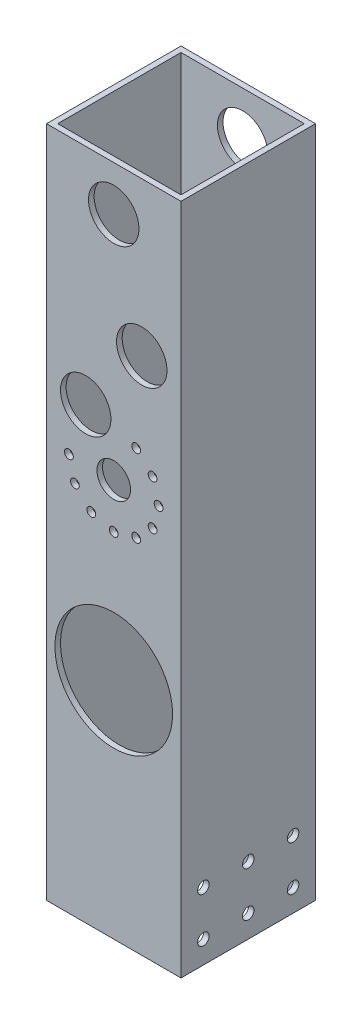
SolidWorks part; units mm, degrees
ref_plane "Front Plane" through (0, 0, 0) normal (0, 0, 1) x (1, 0, 0)
ref_plane "Top Plane" through (0, 0, 0) normal (0, 1, 0) x (1, 0, 0)
ref_plane "Right Plane" through (0, 0, 0) normal (1, 0, 0) x (0, 0, -1)
sketch "Sketch1" plane through (0, 0, 0) normal (0, 1, 0) x (1, 0, 0)
  line L0 (-34.925, -34.925) -> (-34.925, 34.925)
  line L1 (-38.1, -38.1) -> (38.1, -38.1)
  line L2 (-38.1, -38.1) -> (-38.1, 38.1)
  line L3 (-38.1, 38.1) -> (38.1, 38.1)
  line L4 (38.1, -38.1) -> (38.1, 38.1)
  line L5 (-38.1, -38.1) -> (38.1, 38.1) construction
  line L6 (-38.1, 38.1) -> (38.1, -38.1) construction
  line L7 (-34.925, 34.925) -> (34.925, 34.925)
  line L8 (34.925, -34.925) -> (34.925, 34.925)
  line L9 (-34.925, -34.925) -> (34.925, -34.925)
  point P0 (0, 0)
  dimension "D1" = 76.2
  dimension "D2" = 76.2
  dimension "D3" = 3.175
extrude "Boss-Extrude1" add sketch "Sketch1" along normal blind 381
sketch "Sketch2" plane through (0, 0, -38.1) normal (0, 0, -1) x (-1, 0, 0)
  line L0 (-38.1, 381) -> (38.1, 381) construction
  line L1 (-38.1, 381) -> (-38.1, 0) construction
  circle A0 centre (0, 355.6) radius 14.2875
  circle A1 centre (0, 127) radius 9.525
  circle A2 centre (0, 127) radius 25.4 construction
  circle A3 centre (0, 152.4) radius 2.4892
  circle A4 centre (12.7, 148.997) radius 2.4892
  circle A5 centre (21.997, 139.7) radius 2.4892
  circle A6 centre (25.4, 127) radius 2.4892
  circle A7 centre (21.997, 114.3) radius 2.4892
  circle A8 centre (12.7, 105.003) radius 2.4892
  circle A9 centre (0, 101.6) radius 2.4892
  circle A10 centre (-12.7, 105.003) radius 2.4892
  circle A11 centre (-21.997, 114.3) radius 2.4892
  circle A12 centre (-25.4, 127) radius 2.4892
  circle A13 centre (-21.997, 139.7) radius 2.4892
  circle A14 centre (-12.7, 148.997) radius 2.4892
  point P34 (0, 127)
  dimension "D1" = 28.575
  dimension "D4" = 19.05
  dimension "D5" = 50.8
  dimension "D6" = 4.9784
  dimension "D2" = 25.4
  dimension "D3" = 228.6
  dimension "D8" = 12.7
  dimension "D9" = 3.403
  dimension "D10" = 38.1
  dimension "D7" = 12
extrude "Cut-Extrude1" cut sketch "Sketch2" against normal blind 304.8
sketch "Sketch3" plane through (0, 0, 38.1) normal (0, 0, 1) x (1, 0, 0)
  circle A0 centre (0, 127) radius 33.3375
  dimension "D1" = 66.675
extrude "Cut-Extrude2" cut sketch "Sketch3" against normal blind 47.625
sketch "Sketch5" plane through (0, 0, -38.1) normal (0, 0, -1) x (-1, 0, 0)
  line L0 (-38.1, 381) -> (-38.1, 0) construction
  circle A0 centre (-15.875, 294.0377) radius 14.2875
  circle A1 centre (15.875, 254.2844) radius 14.2875
  circle A2 centre (0, 225.244) radius 9.525
  circle A3 centre (0, 355.6) radius 14.2875 construction
  dimension "D4" = 19.05
  dimension "D1" = 63.5762
  dimension "D2" = 50.8762
  dimension "D3" = 33.0962
  dimension "D5" = 22.225
  dimension "D6" = 53.975
  dimension "D7" = 38.1
extrude "Cut-Extrude3" cut sketch "Sketch5" against normal blind 83.185
sketch "Sketch6" plane through (0, 0, -38.1) normal (0, 0, -1) x (-1, 0, 0)
  circle A0 centre (0, 225.244) radius 33.3375
  dimension "D1" = 66.675
extrude "Cut-Extrude4" cut sketch "Sketch6" against normal blind 47.625
sketch "Sketch7" plane through (0, 0, 38.1) normal (0, 0, 1) x (1, 0, 0)
  circle A0 centre (0, 225.244) radius 25.4 construction
  circle A1 centre (0, 199.844) radius 2.4892
  circle A2 centre (-12.7, 203.247) radius 2.4892
  circle A3 centre (-21.997, 212.544) radius 2.4892
  circle A4 centre (-25.4, 225.244) radius 2.4892
  circle A5 centre (-21.997, 237.944) radius 2.4892 [skipped]
  circle A6 centre (-12.7, 247.2411) radius 2.4892 [skipped]
  circle A7 centre (0, 250.644) radius 2.4892 [skipped]
  circle A8 centre (12.7, 247.2411) radius 2.4892
  circle A9 centre (21.997, 237.944) radius 2.4892
  circle A10 centre (25.4, 225.244) radius 2.4892
  circle A11 centre (21.997, 212.544) radius 2.4892
  circle A12 centre (12.7, 203.247) radius 2.4892
  point P30 (0, 225.244)
  dimension "D1" = 50.8
  dimension "D2" = 4.9784
  dimension "D3" = 12
extrude "Cut-Extrude5" cut sketch "Sketch7" against normal blind 47.625
sketch "Sketch10" plane through (-38.1, 0, 0) normal (-1, 0, 0) x (0, 0, 1)
  line L0 (-38.1, 93.6625) -> (38.1, 93.6625) construction
  line L1 (-38.1, 381) -> (-38.1, 0) construction
  line L2 (38.1, 381) -> (38.1, 0) construction
  line L3 (-38.1, 0) -> (38.1, 0) construction
  line L4 (0, 93.6625) -> (0, 0) construction
  line L5 (-38.1, 50.8) -> (38.1, 50.8) construction
  circle A0 centre (-25.4, 12.7) radius 3.2639
  circle A1 centre (0, 12.7) radius 3.2639
  circle A2 centre (25.4, 12.7) radius 3.2639
  circle A3 centre (0, 38.1) radius 3.2639
  circle A4 centre (25.4, 38.1) radius 3.2639
  circle A5 centre (-25.4, 38.1) radius 3.2639
  dimension "D3" = 6.5278
  dimension "D1" = 93.6625
  dimension "D2" = 50.8
  dimension "D4" = 12.7
  dimension "D5" = 12.7
  dimension "D8" = 25.4
  dimension "D9" = 35.921
  dimension "D10" = 25.4
  dimension "D6" = 3
  dimension "D7" = 2
extrude "Cut-Extrude7" cut sketch "Sketch10" against normal through all
